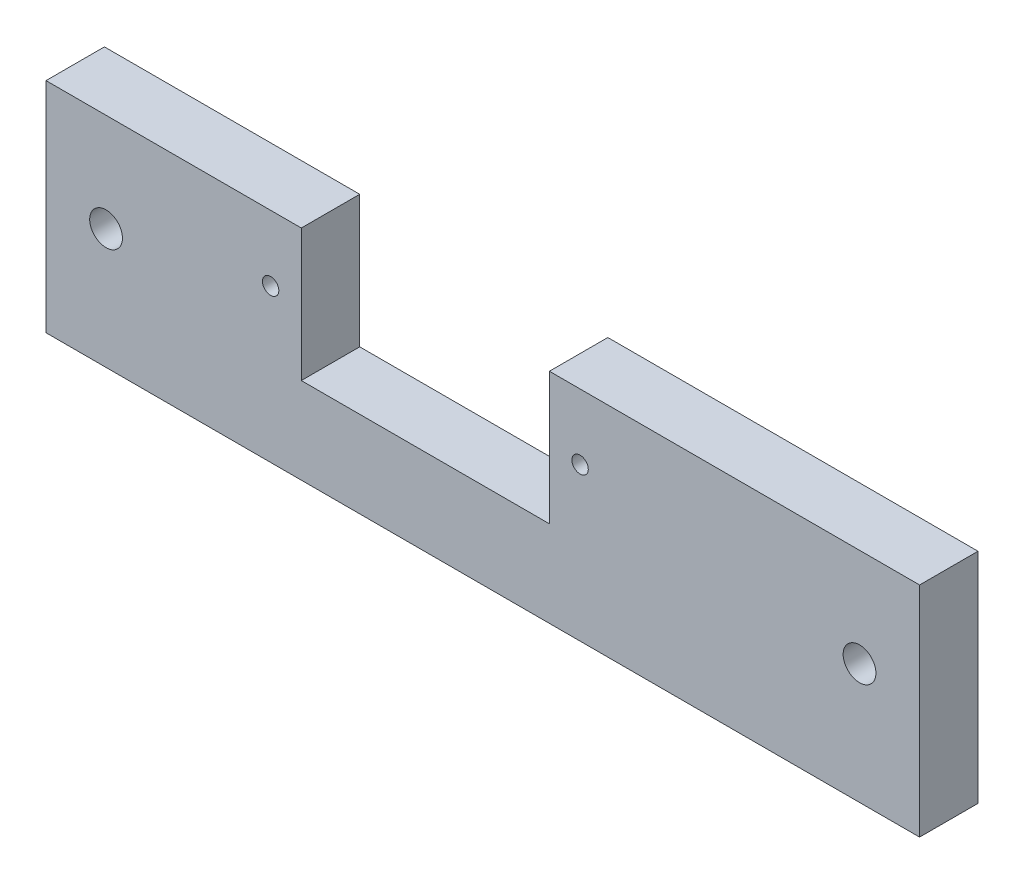
SolidWorks part; units mm, degrees
ref_plane "Front Plane" through (0, 0, 0) normal (0, 0, 1) x (1, 0, 0)
ref_plane "Top Plane" through (0, 0, 0) normal (0, 1, 0) x (1, 0, 0)
ref_plane "Right Plane" through (0, 0, 0) normal (1, 0, 0) x (0, 0, -1)
sketch "Model" plane through (0, 0, 0) normal (0, 0, 1) x (1, 0, 0)
  line L0 (46.1, 20) -> (80, 20)
  line L1 (0, 0) -> (80, 0)
  line L2 (0, 0) -> (0, 20)
  line L3 (0, 20) -> (23.38, 20)
  line L4 (80, 0) -> (80, 20)
  line L5 (40, 0) -> (40, 32.4905) construction
  line L6 (23.38, 20) -> (23.38, 7.9)
  line L7 (23.38, 7.9) -> (46.1, 7.9)
  line L8 (46.1, 20) -> (46.1, 7.9)
  line L9 (34.74, 7.9) -> (34.74, 32.4905) construction
  circle A0 centre (5.5, 11) radius 1.2
  circle A1 centre (5.5, 11) radius 1.5
  circle A2 centre (74.5, 11) radius 1.2
  circle A3 centre (74.5, 11) radius 1.5
  circle A4 centre (20.57, 14) radius 0.75
  circle A5 centre (48.91, 14) radius 0.75
  dimension "D15" = 2.4
  dimension "D17" = 0.3
  dimension "D21" = 1.5
  dimension "D2" = 12.1
  dimension "D4" = 80
  dimension "D6" = 20
  dimension "D8" = 22.72
  dimension "D10" = 23.38
  dimension "D12" = 11
  dimension "D19" = 5.5
  dimension "D23" = 6
  dimension "D24" = 2.81
extrude "Boss-Extrude1" add sketch "Model" along normal blind 5.35 contours L0 L8 L7 L6 L3 L2 L1 L4 A3 A1 A4 A5
equation "\"mdfthick\"=5.35"
equation "\"D1@Boss-Extrude1\"=\"mdfthick\""
